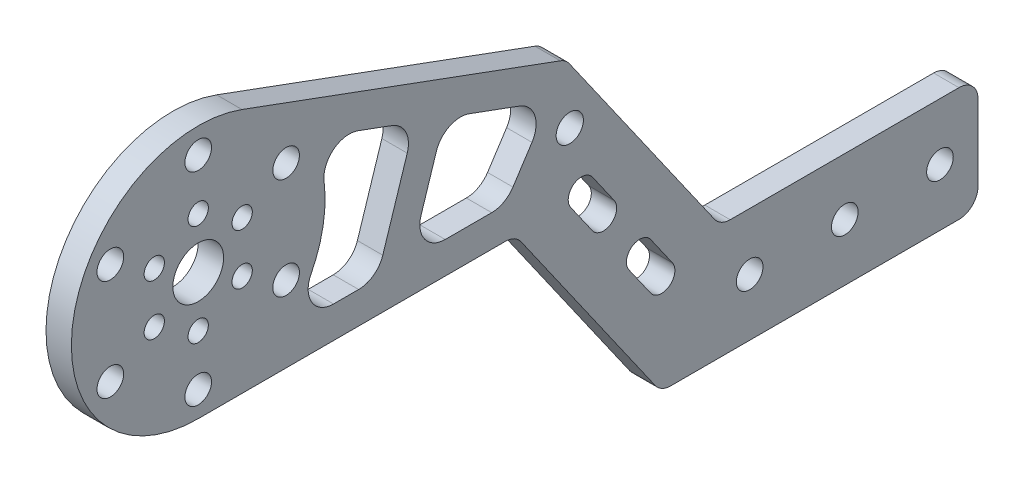
SolidWorks part; units mm, degrees
material "Thornel Mat VMA"
ref_plane "前视基准面" through (0, 0, 0) normal (0, 0, 1) x (1, 0, 0)
ref_plane "上视基准面" through (0, 0, 0) normal (0, 1, 0) x (1, 0, 0)
ref_plane "右视基准面" through (0, 0, 0) normal (1, 0, 0) x (0, 0, -1)
other "Configuration Table"
sketch "草图1" plane through (0, 0, 0) normal (1, 0, 0) x (0, 0, -1)
  line L0 (0, 0) -> (0, 16) construction
  circle A0 centre (0, 0) radius 20
  circle A1 centre (0, 16) radius 2.1
  circle A2 centre (13.8564, 8) radius 2.1
  circle A3 centre (13.8564, -8) radius 2.1
  circle A4 centre (0, -16) radius 2.1
  circle A5 centre (-13.8564, -8) radius 2.1
  circle A6 centre (-13.8564, 8) radius 2.1
  circle A7 centre (0, 8) radius 1.6
  circle A8 centre (6.9282, 4) radius 1.6
  circle A9 centre (6.9282, -4) radius 1.6
  circle A10 centre (0, -8) radius 1.6
  circle A11 centre (-6.9282, -4) radius 1.6
  circle A12 centre (-6.9282, 4) radius 1.6
  circle A13 centre (0, 0) radius 4
  point P17 (0, 0)
  dimension "D1" = 40
  dimension "D2" = 4.2
  dimension "D5" = 3.2
  dimension "D6" = 8
  dimension "D7" = 8
  dimension "D3" = 16
  dimension "D4" = 6
extrude "凸台-拉伸1" add sketch "草图1" along normal blind 4
sketch "草图2" plane through (4, 0, 0) normal (1, 0, 0) x (0, 0, -1)
  line L0 (0, -20) -> (50, -20)
  line L1 (50, -20) -> (72.9431, -52.7661)
  line L2 (20, 0) -> (57.9698, 0)
  line L3 (57.9698, 0) -> (82.3133, -34.7661)
  line L4 (82.3133, -34.7661) -> (122.9431, -34.7661)
  line L5 (122.9431, -34.7661) -> (122.9431, -52.7661)
  line L6 (122.9431, -52.7661) -> (72.9431, -52.7661)
  line L7 (122.9431, -43.7661) -> (77.6282, -43.7661) construction
  line L8 (77.6282, -43.7661) -> (55.0336, -11.4977) construction
  line L9 (6.9001, 18.772) -> (57.9698, 0)
  circle A0 centre (0, 0) radius 20 construction
  circle A2 centre (116.9431, -43.7661) radius 2.1
  circle A3 centre (0, 0) radius 20
  circle A4 centre (0, 0) radius 20
  circle A5 centre (101.9431, -43.7661) radius 2.1
  circle A6 centre (86.9431, -43.7661) radius 2.1
  circle M14 centre (0, 0) radius 20
  dimension "D9" = 4.2
  dimension "D10" = 6
  dimension "D12" = 15
  dimension "D1" = 0
  dimension "D2" = 50
  dimension "D3" = 125
  dimension "D4" = 18
  dimension "D5" = 40
  dimension "D6" = 18
  dimension "D7" = 50
  dimension "D8" = 9
  dimension "D11" = 3
extrude "凸台-拉伸2" add sketch "草图2" against normal blind 4 contours L6 L5 L4 L3 L2 L0 L1 M14 | L9 L2 M14
fillet "圆角1" radius 3 6 edges at (2, -20, -50) (2, -52.7661, -72.9431) (2, -52.7661, -122.9431) (2, -34.7661, -122.9431) (2, -34.7661, -82.3133) (2, 0, -57.9698)
sketch "草图3" plane through (4, 0, 0) normal (1, 0, 0) x (0, 0, -1)
  line L2 (5.1751, 14.079) -> (55.3619, -4.3685)
  line L3 (17.5916, 9.515) -> (55.3619, -4.3685)
  line L4 (55.3619, -4.3685) -> (48.4383, -15)
  line L5 (0, -15) -> (48.4383, -15)
  line L6 (13.2288, -15) -> (48.4383, -15)
  line L7 (62.2003, -37.5883) -> (77.0223, -27.2098) construction
  line L8 (50.8958, -21.2793) -> (72.0473, -51.4868) construction
  line L9 (58.5093, -0.7705) -> (81.4175, -33.4868) construction
  line L10 (69.6113, -32.3991) -> (73.0528, -37.314) construction
  line L11 (71.3315, -31.1946) -> (74.773, -36.1095)
  line L12 (67.8911, -33.6036) -> (71.3326, -38.5185)
  line L13 (60.4341, -19.2926) -> (63.8755, -24.2076) construction
  line L14 (62.1543, -18.0881) -> (65.5958, -23.003)
  line L15 (58.7139, -20.4971) -> (62.1553, -25.4121)
  line L16 (42.12, 20.1465) -> (30.8335, -15)
  line L17 (39.7397, 20.9109) -> (27.2146, -18.0928)
  line L18 (44.5002, 19.3821) -> (33.2138, -15.7644)
  line L19 (39.7397, 20.9109) -> (28.4532, -14.2356) construction
  circle A0 centre (0, 0) radius 20
  arc A1 (71.3315, -31.1946) -> (67.8911, -33.6036) centre (69.6113, -32.3991) ccw
  arc A2 (71.3326, -38.5185) -> (74.773, -36.1095) centre (73.0528, -37.314) ccw
  arc A3 (62.1543, -18.0881) -> (58.7139, -20.4971) centre (60.4341, -19.2926) ccw
  arc A4 (62.1553, -25.4121) -> (65.5958, -23.003) centre (63.8755, -24.2076) ccw
  point P15 (71.332, -34.8565)
  point P24 (62.1548, -21.7501)
  point P32 (36.4767, 2.5733)
  dimension "D1" = 5
  dimension "D3" = 40
  dimension "D4" = 2.1
  dimension "D5" = 6
  dimension "D7" = 2.5
  dimension "D2" = 5
  dimension "D8" = 2.5
  dimension "D6" = 2
extrude "切除-拉伸1" cut sketch "草图3" against normal blind 4 contours A0 L6 L17 L3 | L3 L18 L6 L4 | L15 A4 L14 A3 | L12 A2 L11 A1
fillet "圆角2" radius 4 8 edges at (2, -4.3685, -55.3619) (2, -15, -48.4383) (2, -15, -33.4593) (2, 1.71, -38.8253) (2, 9.515, -17.5916) (2, 3.4365, -34.1282) (2, -15, -28.2078) (2, -15, -13.2288)
sketch "草图4" plane through (4, 0, 0) normal (1, 0, 0) x (0, 0, -1)
  line L0 (58.5093, -0.7705) -> (81.4175, -33.4868) construction
  circle A0 centre (58.5788, -9.5869) radius 2.15
  dimension "D1" = 4.3
  dimension "D2" = 5
extrude "切除-拉伸2" cut sketch "草图4" against normal blind 4
